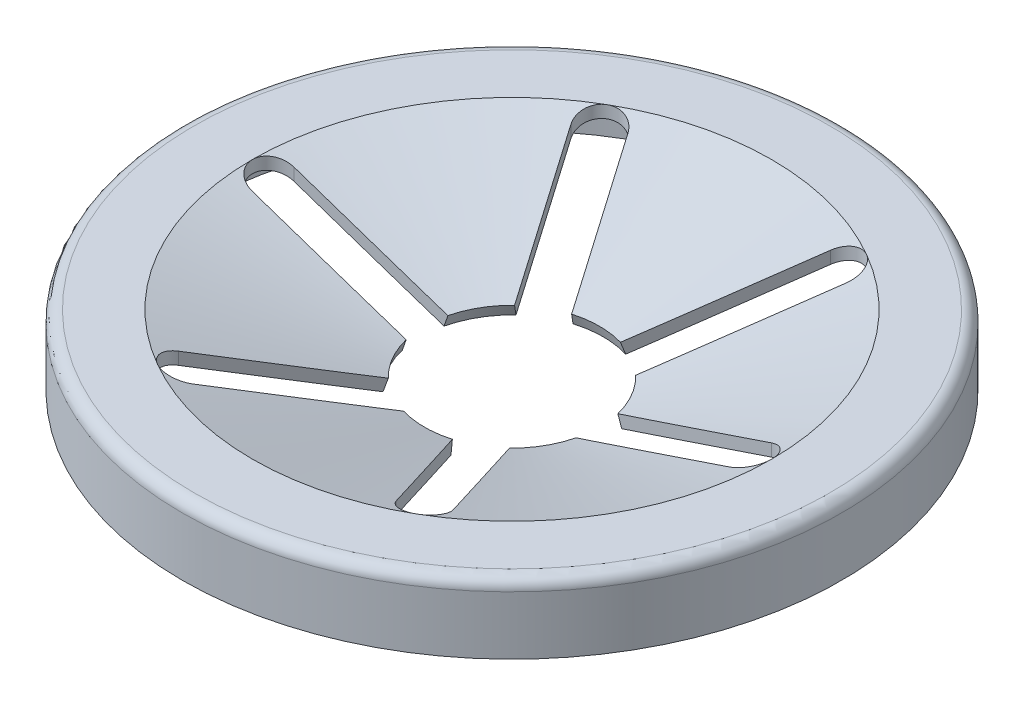
SolidWorks part; units mm, degrees
ref_plane "Front" through (0, 0, 0) normal (0, 0, 1) x (1, 0, 0)
ref_plane "Top" through (0, 0, 0) normal (0, 1, 0) x (1, 0, 0)
ref_plane "Right" through (0, 0, 0) normal (1, 0, 0) x (0, 0, -1)
sketch "Support-Top-Washer" plane through (0, 0, 0) normal (0, 1, 0) x (1, 0, 0)
  line L0 (0, 0) -> (5.65, 0) construction
  circle A0 centre (0, 0) radius 5.65
  circle A1 centre (0, 0) radius 1.5
  dimension "Diam-Inner" = 3
  dimension "Diam-Outer" = 11.3
sketch "Support-Front-Profile" plane through (0, 0, 0) normal (0, 0, 1) x (1, 0, 0)
  line L0 (0, 0) -> (5.65, 0) construction
  line L1 (4.45, 1.2) -> (5.65, 1.2)
  line L2 (4.45, 1.2) -> (1.5, 0.2)
  line L3 (1.5, 0) -> (1.5, 0.2) construction
  line L4 (5.65, 1.2) -> (5.65, 0)
  line L5 (4.45, 1.2) -> (4.45, 1) construction
  line L6 (4.45, 1.2) -> (4.45, 0) construction
  line L7 (4.45, 1) -> (5.45, 1) construction
  line L10 (0, 0) -> (5.65, 0) construction
  arc A0 (5.45, 1.2) -> (5.65, 1) centre (5.45, 1) cw
  dimension "Thickness" = 0.2
  dimension "Heigth" = 1.2
sketch "Support-Top-Slit" plane through (0, 0, 0) normal (0, 1, 0) x (1, 0, 0)
  line L1 (4.45, 0) -> (0, 0) construction
  line L5 (4.092, 0.358) -> (1.4567, 0.358)
  line L7 (0, 0) -> (4.092, 0.358) construction
  line L11 (4.092, -0.358) -> (1.4567, -0.358)
  circle A1 centre (0, 0) radius 1.5 construction
  arc A5 (1.4567, -0.358) -> (1.4567, 0.358) centre (0, 0) ccw
  arc A6 (4.092, 0.358) -> (4.092, -0.358) centre (4.092, 0) cw
  dimension "D1" = 5
sketch "Sketch4" plane through (0, 0, 0) normal (0, 0, 1) x (1, 0, 0)
  line L1 (5.65, 1.2) -> (5.65, 0) construction
  line L2 (4.45, 1.2) -> (5.65, 1.2) construction
  line L3 (4.45, 1.2) -> (1.5, 0.2) construction
  line L5 (5.65, 1) -> (5.65, 0)
  line L6 (4.45, 1.2) -> (5.45, 1.2)
  line L7 (4.45, 1.2) -> (1.5, 0.2)
  line L8 (0, 1.2) -> (0, 0) construction
  arc A0 (5.65, 1) -> (5.45, 1.2) centre (5.45, 1) ccw construction
  arc A1 (5.65, 1) -> (5.45, 1.2) centre (5.45, 1) ccw
revolve "Body-Washer" add sketch "Sketch4" angle 360 about L8
sketch "Sketch5" plane through (0, 0, 0) normal (0, 1, 0) x (1, 0, 0)
  line L6 (4.092, 0.358) -> (1.4567, 0.358)
  line L8 (1.4567, -0.358) -> (4.092, -0.358)
  line L9 (4.092, 0.358) -> (1.4567, 0.358)
  line L11 (1.4567, -0.358) -> (4.092, -0.358)
  arc A5 (1.4567, -0.358) -> (1.4567, 0.358) centre (0, 0) ccw
  arc A7 (4.092, -0.358) -> (4.092, 0.358) centre (4.092, 0) ccw
  arc A8 (1.4567, -0.358) -> (1.4567, 0.358) centre (0, 0) ccw
  arc A9 (4.092, -0.358) -> (4.092, 0.358) centre (4.092, 0) ccw
  dimension "D1" = 0
extrude "Cut-Slit" cut sketch "Sketch5" along normal through all
pattern_circular "Pattern-Cut-Slit" count 6 over 360 about axis through (0, 0, 0) along (0, 1, 0) of "Cut-Slit"
equation "\"D3@Body-Washer\" = \"Thickness@Support-Front-Profile\""
